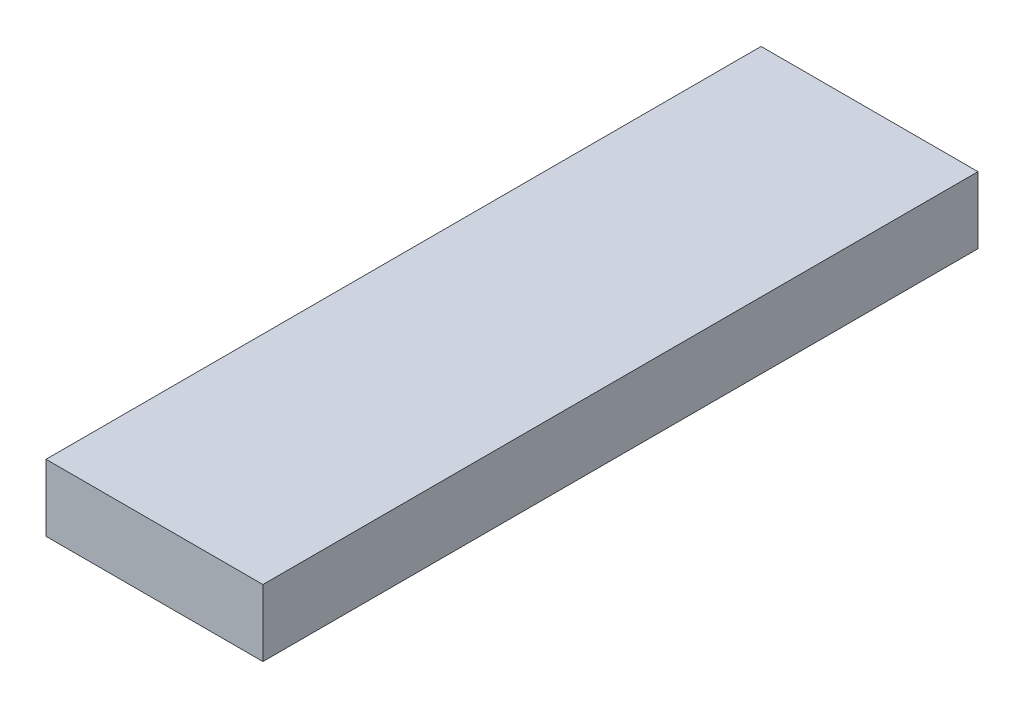
SolidWorks part; units mm, degrees
ref_plane "Front Plane" through (0, 0, 0) normal (0, 0, 1) x (1, 0, 0)
ref_plane "Top Plane" through (0, 0, 0) normal (0, 1, 0) x (1, 0, 0)
ref_plane "Right Plane" through (0, 0, 0) normal (1, 0, 0) x (0, 0, -1)
sketch "Sketch1" plane through (0, 0, 0) normal (0, 1, 0) x (1, 0, 0)
  line L1 (11.557, 38.1) -> (-11.557, 38.1)
  line L2 (11.557, 38.1) -> (11.557, -38.1)
  line L3 (11.557, -38.1) -> (-11.557, -38.1)
  line L4 (-11.557, 38.1) -> (-11.557, -38.1)
  line L5 (11.557, 38.1) -> (-11.557, -38.1) construction
  line L6 (11.557, -38.1) -> (-11.557, 38.1) construction
  point P0 (0, 0)
  dimension "D1" = 76.2
  dimension "D2" = 23.114
extrude "Boss-Extrude1" add sketch "Sketch1" along normal blind 7.112
